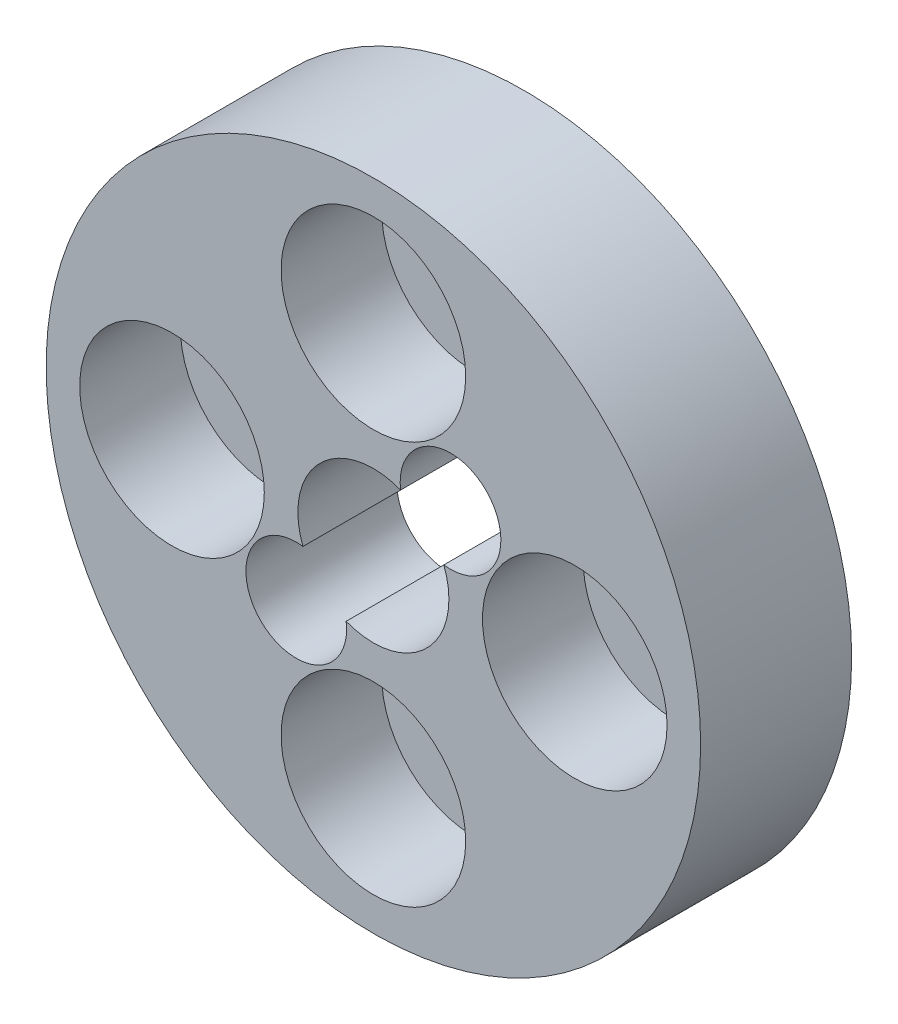
SolidWorks part; units mm, degrees
ref_plane "Front Plane" through (0, 0, 0) normal (0, 0, 1) x (1, 0, 0)
ref_plane "Top Plane" through (0, 0, 0) normal (0, 1, 0) x (1, 0, 0)
ref_plane "Right Plane" through (0, 0, 0) normal (1, 0, 0) x (0, 0, -1)
sketch "Sketch1" plane through (0, 0, 0) normal (0, 0, 1) x (1, 0, 0)
  circle A0 centre (0, 0) radius 2.25
  circle A1 centre (0, 0) radius 9.75
  circle A2 centre (0, 0) radius 6 construction
  circle A3 centre (0, 6) radius 1.5
  circle A4 centre (6, 0) radius 1.5
  circle A5 centre (0, -6) radius 1.5
  circle A6 centre (-6, 0) radius 1.5
  point P16 (0, 0)
  dimension "D1" = 4.5
  dimension "D2" = 19.5
  dimension "D3" = 12
  dimension "D4" = 3
  dimension "D5" = 4
extrude "Boss-Extrude1" add sketch "Sketch1" along normal blind 4.5
sketch "Sketch2" plane through (0, 0, 4.5) normal (0, 0, 1) x (1, 0, 0)
  line L0 (0, 0) -> (-0.761, -0.761) construction
  line L1 (0, 0) -> (-1.1762, 0) construction
  circle A0 centre (0, 0) radius 3.25 construction
  circle A1 centre (2.2981, 2.2981) radius 1.5
  circle A2 centre (-2.2981, -2.2981) radius 1.5
  dimension "D1" = 6.5
  dimension "D3" = 3
  dimension "D2" = 45
extrude "Cut-Extrude1" cut sketch "Sketch2" against normal through all
chamfer "Chamfer1" [suppressed] distance 1 angle 45
sketch "Sketch3" plane through (0, 0, 4.5) normal (0, 0, 1) x (1, 0, 0)
  circle A0 centre (0, 6) radius 1.5 construction
  circle A1 centre (-6, 0) radius 1.5 construction
  circle A2 centre (0, -6) radius 1.5 construction
  circle A3 centre (6, 0) radius 1.5 construction
  circle A4 centre (0, 6) radius 1.5 construction
  circle A5 centre (-6, 0) radius 1.5 construction
  circle A6 centre (0, -6) radius 1.5 construction
  circle A7 centre (6, 0) radius 1.5 construction
  circle A8 centre (6, 0) radius 2.75
  circle A9 centre (0, -6) radius 2.75
  circle A10 centre (-6, 0) radius 2.75
  circle A11 centre (0, 6) radius 2.75
  dimension "D1" = 5.5
extrude "Cut-Extrude2" cut sketch "Sketch3" against normal blind 3
